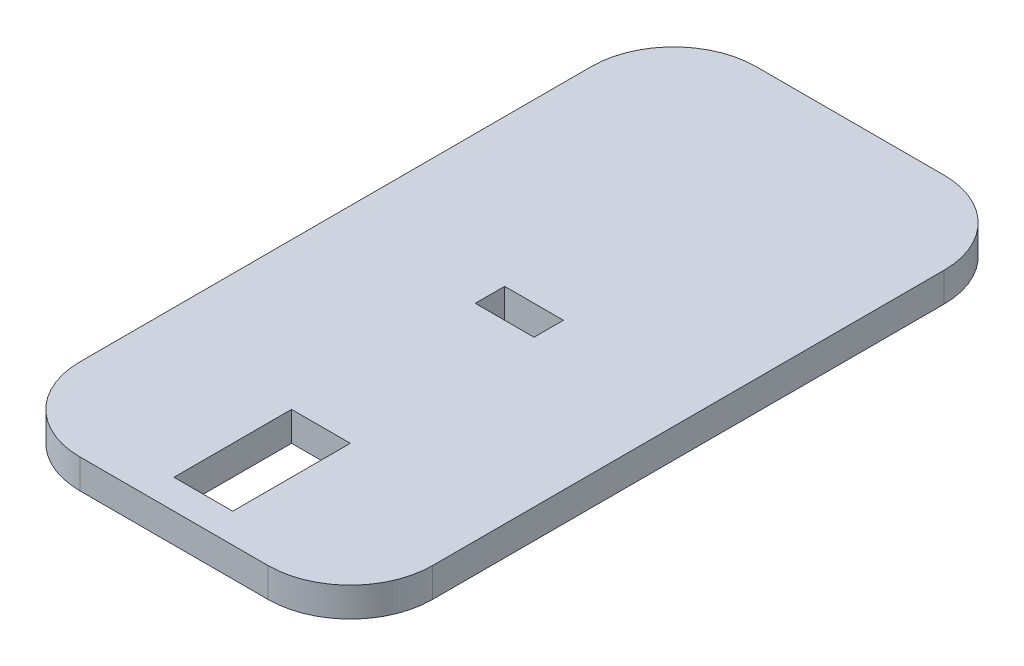
SolidWorks part; units mm, degrees
ref_plane "Front Plane" through (0, 0, 0) normal (0, 0, 1) x (1, 0, 0)
ref_plane "Top Plane" through (0, 0, 0) normal (0, 1, 0) x (1, 0, 0)
ref_plane "Right Plane" through (0, 0, 0) normal (1, 0, 0) x (0, 0, -1)
sketch "Sketch1" plane through (0, 0, 0) normal (0, 1, 0) x (1, 0, 0)
  line L0 (38.1, 152.4) -> (38.1, 100.0125) construction
  line L1 (0, 134.62) -> (0, 24.13) construction
  line L2 (0, 24.13) -> (0, 134.62)
  line L3 (17.78, 152.4) -> (58.42, 152.4)
  line L4 (76.2, 24.13) -> (76.2, 134.62)
  line L5 (38.1, 0) -> (38.1, 25.4) construction
  line L6 (0, 80.9625) -> (76.2, 80.9625) construction
  line L7 (17.78, 6.35) -> (58.42, 6.35) construction
  line L8 (31.75, 77.7875) -> (44.45, 77.7875)
  line L9 (31.75, 77.7875) -> (31.75, 84.1375)
  line L10 (31.75, 84.1375) -> (44.45, 84.1375)
  line L11 (44.45, 77.7875) -> (44.45, 84.1375)
  line L12 (31.75, 77.7875) -> (44.45, 84.1375) construction
  line L13 (31.75, 84.1375) -> (44.45, 77.7875) construction
  line L14 (31.75, 12.7) -> (44.45, 12.7)
  line L15 (31.75, 12.7) -> (31.75, 38.1)
  line L16 (31.75, 38.1) -> (44.45, 38.1)
  line L17 (44.45, 12.7) -> (44.45, 38.1)
  line L18 (31.75, 12.7) -> (44.45, 38.1) construction
  line L19 (31.75, 38.1) -> (44.45, 12.7) construction
  line L20 (17.78, 6.35) -> (58.42, 6.35)
  line L21 (0, 79.375) -> (76.2, 79.375) construction
  arc A0 (0, 24.13) -> (17.78, 6.35) centre (17.78, 24.13) ccw construction
  arc A1 (0, 24.13) -> (17.78, 6.35) centre (17.78, 24.13) ccw
  arc A2 (58.42, 6.35) -> (76.2, 24.13) centre (58.42, 24.13) ccw construction
  arc A3 (58.42, 6.35) -> (76.2, 24.13) centre (58.42, 24.13) ccw
  arc A4 (58.42, 152.4) -> (76.2, 134.62) centre (58.42, 134.62) cw
  arc A5 (0, 134.62) -> (17.78, 152.4) centre (17.78, 134.62) cw
  point P0 (0, 79.375)
  point P11 (38.1, 80.9625)
  dimension "D3" = 71.4375
  dimension "D5" = 6.35
  dimension "D6" = 12.7
  dimension "D4" = 12.7
  dimension "D7" = 25.4
  dimension "D8" = 25.4
extrude "Boss-Extrude1" add sketch "Sketch1" along normal blind 6.35
